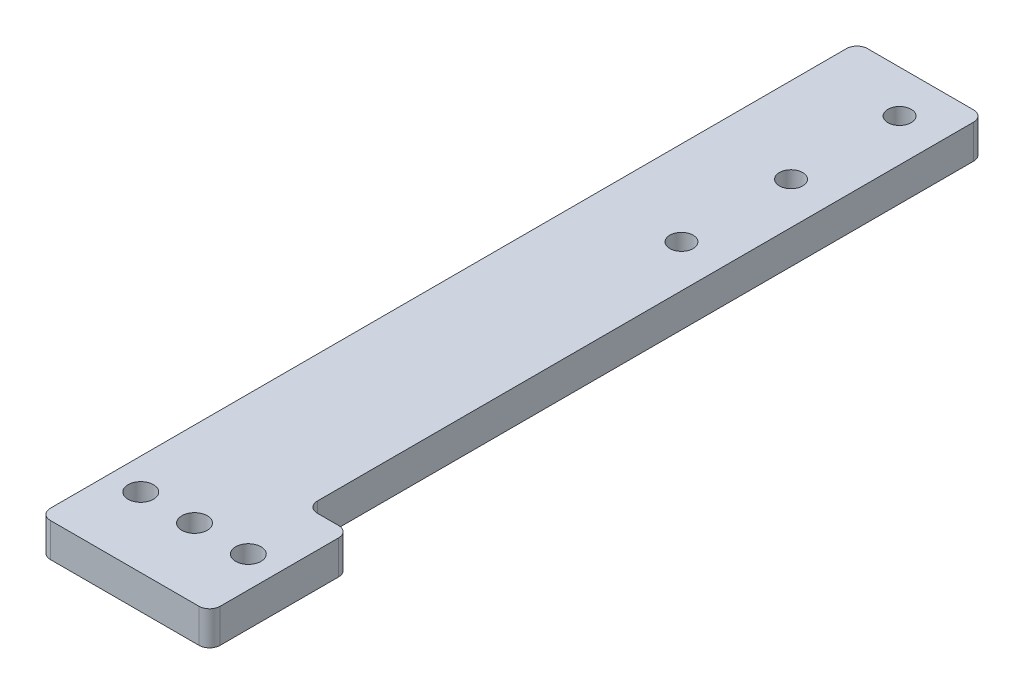
SolidWorks part; units mm, degrees
ref_plane "前视基准面" through (0, 0, 0) normal (0, 0, 1) x (1, 0, 0)
ref_plane "上视基准面" through (0, 0, 0) normal (0, 1, 0) x (1, 0, 0)
ref_plane "右视基准面" through (0, 0, 0) normal (1, 0, 0) x (0, 0, -1)
sketch "草图1" plane through (0, 0, 0) normal (0, 1, 0) x (1, 0, 0)
  line L0 (0, 10.8478) -> (0, -12.0384) construction
  line L1 (-2, -16) -> (2, -16)
  line L2 (-2, -16) -> (-2, 16)
  line L3 (-2, 16) -> (2, 16)
  line L4 (2, -16) -> (2, 16)
  line L5 (-2, -16) -> (2, 16) construction
  line L6 (-2, 16) -> (2, -16) construction
  line L7 (-0.8192, 8.8501) -> (0.8674, 8.8501) construction
  circle A0 centre (0.0241, 8.8501) radius 0.55
  circle A1 centre (0, 14) radius 0.55
  circle A2 centre (0, 3.7001) radius 0.55
  point P0 (0, 0)
  dimension "D2" = 1.1
  dimension "D3" = 1.1
  dimension "D4" = 5.15
  dimension "D5" = 2
  dimension "D1" = 4
  dimension "D6" = 32
extrude "凸台-拉伸1" add sketch "草图1" along normal blind 1.6
sketch "草图3" plane through (0, 0, 0) normal (0, 1, 0) x (1, 0, 0)
  line L0 (0, -16) -> (0, -22.6) construction
  line L1 (-2, -16) -> (2, -16) construction
  line L2 (0, -19.3) -> (-4.01, -19.3) construction
  line L3 (-4.01, -19.3) -> (-4.01, -16) construction
  line L4 (-4.01, -16) -> (0, -16) construction
  line L6 (4.01, -22.6) -> (-4.01, -22.6)
  line L7 (4.01, -22.6) -> (4.01, -16)
  line L8 (4.01, -16) -> (-4.01, -16)
  line L9 (-4.01, -22.6) -> (-4.01, -16)
  line L10 (4.01, -22.6) -> (-4.01, -16) construction
  line L11 (4.01, -16) -> (-4.01, -22.6) construction
  dimension "D1" = 6.6
  dimension "D2" = 4.01
extrude "凸台-拉伸2" add sketch "草图3" along normal blind 1.6
sketch "草图4" plane through (0, 1.6, 0) normal (0, 1, 0) x (1, 0, 0)
  line L0 (-4.01, -19.3) -> (4.01, -19.3) construction
  line L1 (-4.01, -16) -> (-4.01, -22.6) construction
  line L2 (4.01, -22.6) -> (4.01, -16) construction
  line L3 (0, -16.9967) -> (0, -21.5738) construction
  circle A0 centre (0, -19.3) radius 0.6
  circle A1 centre (-2.54, -19.3) radius 0.6
  circle A2 centre (2.54, -19.3) radius 0.6
  dimension "D1" = 1.2
  dimension "D2" = 1.2
  dimension "D3" = 5.08
extrude "切除-拉伸1" cut sketch "草图4" against normal blind 1.6
sketch "草图6" plane through (0, 0, 0) normal (0, 1, 0) x (1, 0, 0)
  line L0 (-4.01, -16) -> (-4.01, 16.6945) construction
  line L1 (-2, 16) -> (-4.01, 16) construction
  line L3 (-4.01, 16) -> (-2, 16)
  line L4 (-4.01, 16) -> (-4.01, -16)
  line L5 (-4.01, -16) -> (-2, -16)
  line L6 (-2, 16) -> (-2, -16)
extrude "凸台-拉伸3" add sketch "草图6" along normal blind 1.6
fillet "圆角1" radius 0.5 6 edges at (-4.01, 0.8, 22.6) (4.01, 0.8, 22.6) (4.01, 0.8, 16) (2, 0.8, 16) (2, 0.8, -16) (-4.01, 0.8, -16)
